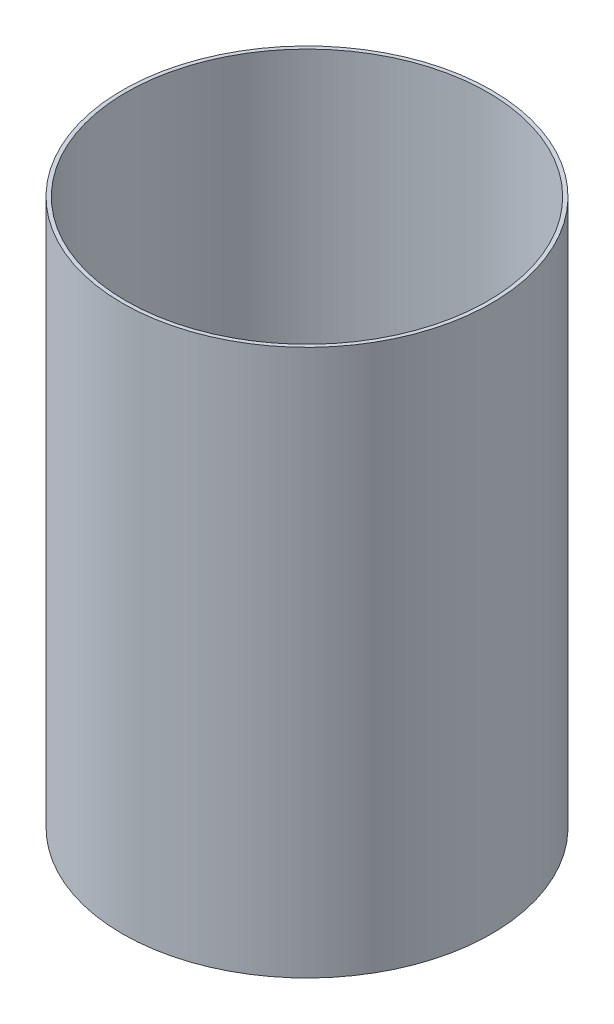
SolidWorks part; units mm, degrees
ref_plane "Front Plane" through (0, 0, 0) normal (0, 0, 1) x (1, 0, 0)
ref_plane "Top Plane" through (0, 0, 0) normal (0, 1, 0) x (1, 0, 0)
ref_plane "Right Plane" through (0, 0, 0) normal (1, 0, 0) x (0, 0, -1)
sketch "Sketch1" plane through (0, 0, 0) normal (0, 1, 0) x (1, 0, 0)
  circle A0 centre (0, 0) radius 248.92
extrude "Boss-Extrude1" add sketch "Sketch1" along normal blind 736.6
sketch "Sketch2" plane through (0, 736.6, 0) normal (0, 1, 0) x (1, 0, 0)
  circle A0 centre (0, 0) radius 243.84
extrude "Cut-Extrude1" cut sketch "Sketch2" against normal blind 711.2
